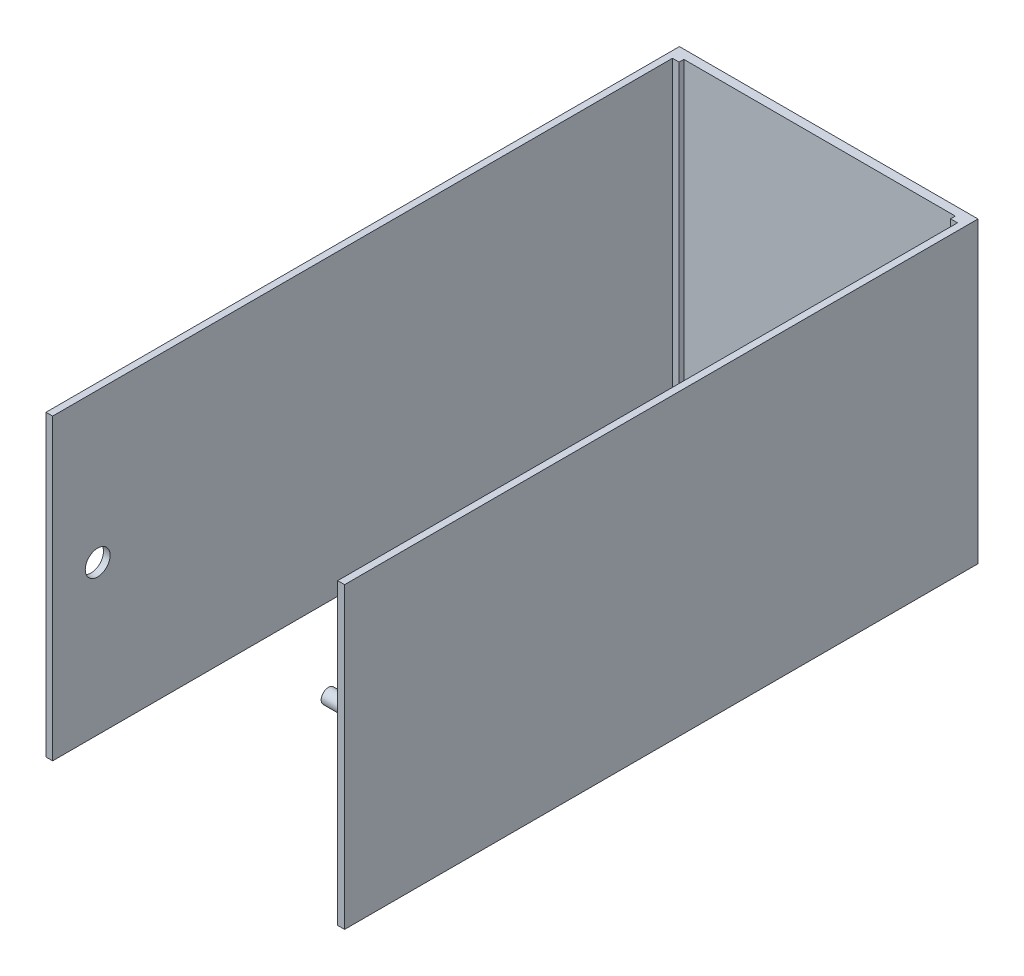
SolidWorks part; units mm, degrees
ref_plane "Plano frontal" through (0, 0, 0) normal (0, 0, 1) x (1, 0, 0)
ref_plane "Plano superior" through (0, 0, 0) normal (0, 1, 0) x (1, 0, 0)
ref_plane "Plano direito" through (0, 0, 0) normal (1, 0, 0) x (0, 0, -1)
sketch "Esboço1" plane through (0, 0, 0) normal (0, 0, 1) x (1, 0, 0)
  circle A0 centre (0, 0) radius 5
  dimension "D1" = 10
extrude "Ressalto-extrusão2" add sketch "Esboço1" along normal blind 10
sketch "Esboço3" plane through (0, 0, 0) normal (0, 0, -1) x (-1, 0, 0)
  circle A0 centre (0, 0) radius 2.5
  dimension "D1" = 5
extrude "Corte-extrusão2" cut sketch "Esboço3" against normal blind 3
sketch "Esboço4" plane through (0, 0, 10) normal (0, 0, 1) x (1, 0, 0)
  line L1 (33, 33) -> (-33, 33)
  line L2 (33, 33) -> (33, -33)
  line L3 (33, -33) -> (-33, -33)
  line L4 (-33, 33) -> (-33, -33)
  line L5 (33, 33) -> (-33, -33) construction
  line L6 (33, -33) -> (-33, 33) construction
  point P0 (0, 0)
  dimension "D1" = 66
  dimension "D2" = 66
extrude "Ressalto-extrusão3" add sketch "Esboço4" along normal blind 60
sketch "Esboço5" plane through (0, 0, 70) normal (0, 0, 1) x (1, 0, 0)
  line L1 (30, 31.5) -> (-30, 31.5)
  line L2 (30, 31.5) -> (30, -31.5)
  line L3 (30, -31.5) -> (-30, -31.5)
  line L4 (-30, 31.5) -> (-30, -31.5)
  line L5 (30, 31.5) -> (-30, -31.5) construction
  line L6 (30, -31.5) -> (-30, 31.5) construction
  point P0 (0, 0)
  dimension "D1" = 60
  dimension "D2" = 63
extrude "Corte-extrusão3" cut sketch "Esboço5" against normal blind 57
sketch "Esboço6" plane through (0, 33, 0) normal (0, 1, 0) x (1, 0, 0)
  line L1 (29.942, -11.9562) -> (-30.058, -11.9562)
  line L2 (29.942, -11.9562) -> (29.942, -70.9562)
  line L3 (29.942, -70.9562) -> (-30.058, -70.9562)
  line L4 (-30.058, -11.9562) -> (-30.058, -70.9562)
  line L5 (29.942, -11.9562) -> (-30.058, -70.9562) construction
  line L6 (29.942, -70.9562) -> (-30.058, -11.9562) construction
  point P0 (-0.058, -41.4562)
  point P5 (0, 0)
  point P6 (0, 0)
  dimension "D1" = 60
  dimension "D2" = 59
extrude "Corte-extrusão5" cut sketch "Esboço6" against normal blind 84
sketch "Esboço7" plane through (0, 0, 70) normal (0, 0, 1) x (1, 0, 0)
  line L1 (-33, 33) -> (-30.058, 33)
  line L2 (-33, 33) -> (-33, -33)
  line L3 (-33, -33) -> (-30.058, -33)
  line L4 (-30.058, 33) -> (-30.058, -33)
  line L5 (33, 33) -> (29.942, 33)
  line L6 (33, 33) -> (33, -33)
  line L7 (33, -33) -> (29.942, -33)
  line L8 (29.942, 33) -> (29.942, -33)
extrude "Ressalto-extrusão4" add sketch "Esboço7" along normal blind 80
sketch "Esboço8" plane through (0, 0, 150) normal (0, 0, 1) x (1, 0, 0)
  line L0 (-33, -33) -> (-30.058, -33) construction
  line L1 (-30.058, 33) -> (-31.529, 33)
  line L2 (-30.058, 33) -> (-30.058, -33)
  line L3 (-30.058, -33) -> (-31.529, -33)
  line L4 (-31.529, 33) -> (-31.529, -33)
  line L5 (29.942, -33) -> (33, -33) construction
  line L6 (29.942, 33) -> (31.471, 33)
  line L7 (29.942, 33) -> (29.942, -33)
  line L8 (29.942, -33) -> (31.471, -33)
  line L9 (31.471, 33) -> (31.471, -33)
extrude "Corte-extrusão6" cut sketch "Esboço8" against normal blind 137
sketch "Esboço9" plane through (-33, 0, 0) normal (-1, 0, 0) x (0, 0, 1)
  circle A0 centre (140.048, 0) radius 2.75
  dimension "D1" = 5.5
extrude "Corte-extrusão7" cut sketch "Esboço9" against normal blind 49
sketch "Esboço10" plane through (31.471, 0, 0) normal (-1, 0, 0) x (0, 0, 1)
  circle A0 centre (140.048, 0) radius 1.6
  dimension "D1" = 3.2
extrude "Ressalto-extrusão5" add sketch "Esboço10" along normal blind 12
